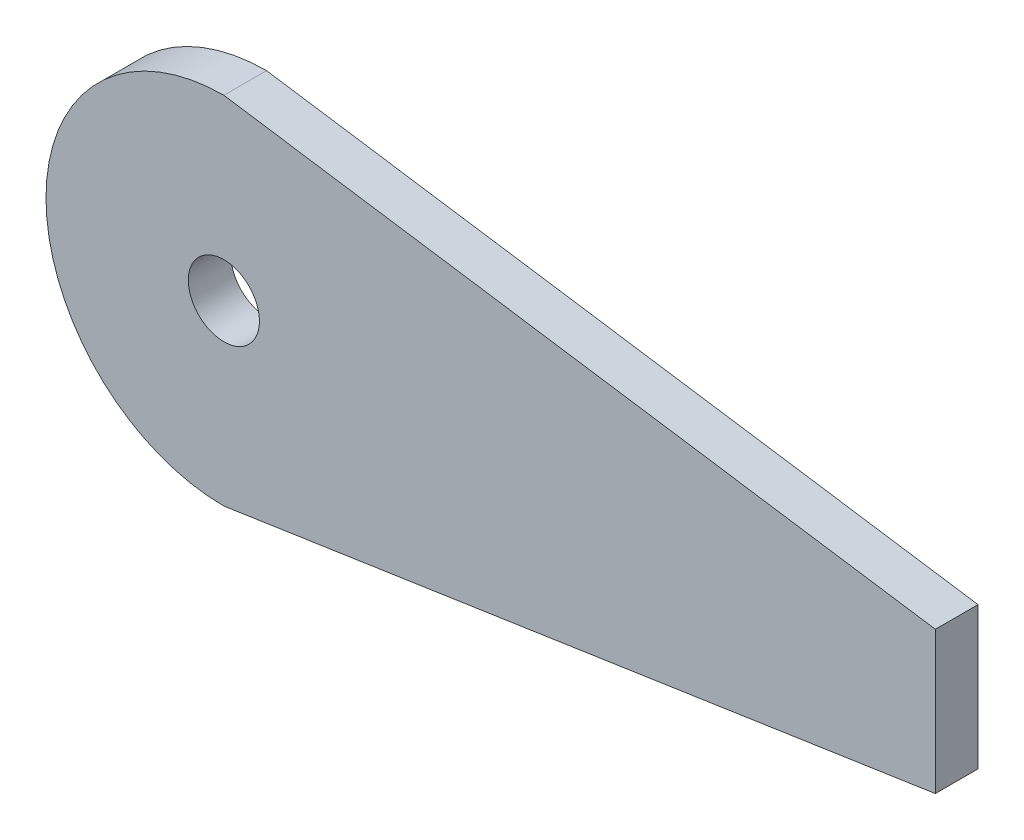
SolidWorks part; units mm, degrees
material "Acrylic (Medium-high impact)"
ref_plane "Front Plane" through (0, 0, 0) normal (0, 0, 1) x (1, 0, 0)
ref_plane "Top Plane" through (0, 0, 0) normal (0, 1, 0) x (1, 0, 0)
ref_plane "Right Plane" through (0, 0, 0) normal (1, 0, 0) x (0, 0, -1)
sketch "Sketch1" plane through (0, 0, 0) normal (0, 0, 1) x (1, 0, 0)
  line L0 (0, 12.5) -> (50, 5)
  line L1 (50, -5) -> (0, -12.5)
  line L2 (0, 0) -> (50, 0) construction
  line L3 (50, 5) -> (50, -5)
  circle A0 centre (0, 0) radius 2.5
  arc A1 (0, 12.5) -> (0, -12.5) centre (0, 0) ccw
  point P5 (50, 0)
  dimension "D1" = 5
  dimension "D2" = 10
  dimension "D3" = 10
  dimension "D4" = 50
extrude "Boss-Extrude1" add sketch "Sketch1" along normal blind 3
